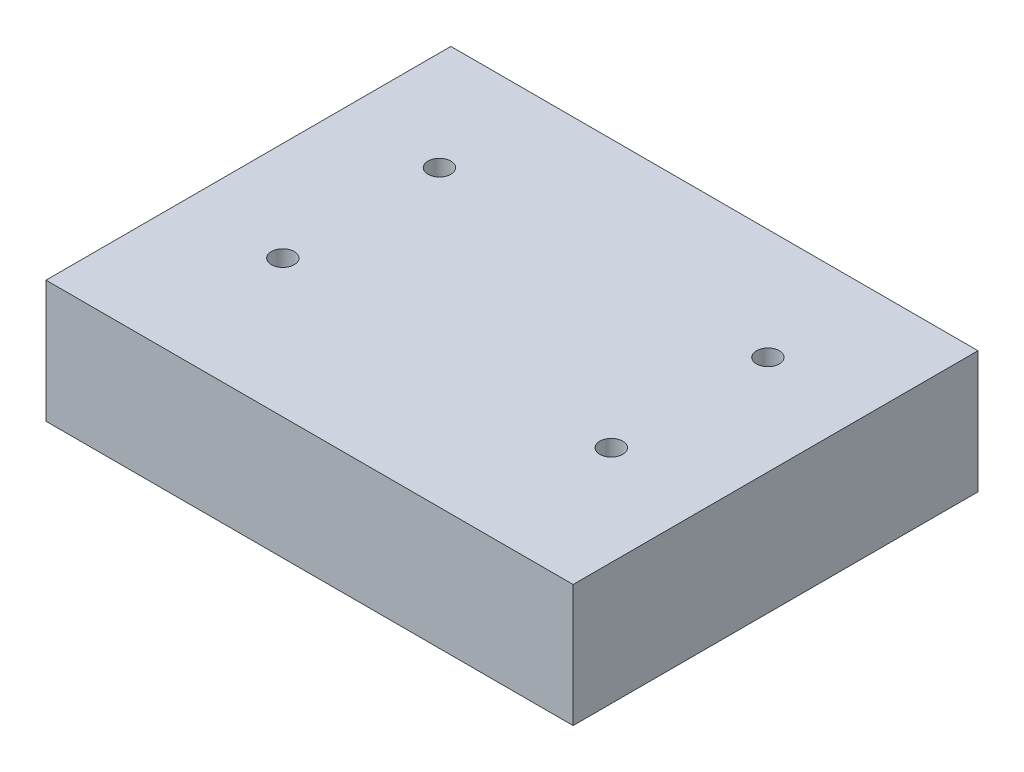
SolidWorks part; units mm, degrees
ref_plane "Front Plane" through (0, 0, 0) normal (0, 0, 1) x (1, 0, 0)
ref_plane "Top Plane" through (0, 0, 0) normal (0, 1, 0) x (1, 0, 0)
ref_plane "Right Plane" through (0, 0, 0) normal (1, 0, 0) x (0, 0, -1)
sketch "Sketch2" plane through (0, 0, 0) normal (0, 1, 0) x (1, 0, 0)
  line L0 (0, 1325) -> (0, -1325) construction
  line L1 (1725, -1325) -> (-1725, -1325)
  line L2 (1725, -1325) -> (1725, 1325)
  line L3 (1725, 1325) -> (-1725, 1325)
  line L4 (-1725, -1325) -> (-1725, 1325)
  line L5 (1725, -1325) -> (-1725, 1325) construction
  line L6 (1725, 1325) -> (-1725, -1325) construction
  line L7 (-1725, 0) -> (1725, 0) construction
  circle A0 centre (1075, -425) radius 75
  circle A1 centre (1075, 600) radius 75
  circle A2 centre (-1075, -425) radius 75
  circle A3 centre (-1075, 600) radius 75
  point P0 (0, 0)
  dimension "D3" = 150
  dimension "D6" = 150
  dimension "D1" = 3450
  dimension "D2" = 2650
  dimension "D4" = 1075
  dimension "D5" = 900
  dimension "D7" = 1075
  dimension "D8" = 1025
extrude "Boss-Extrude1" add sketch "Sketch2" along normal blind 800
